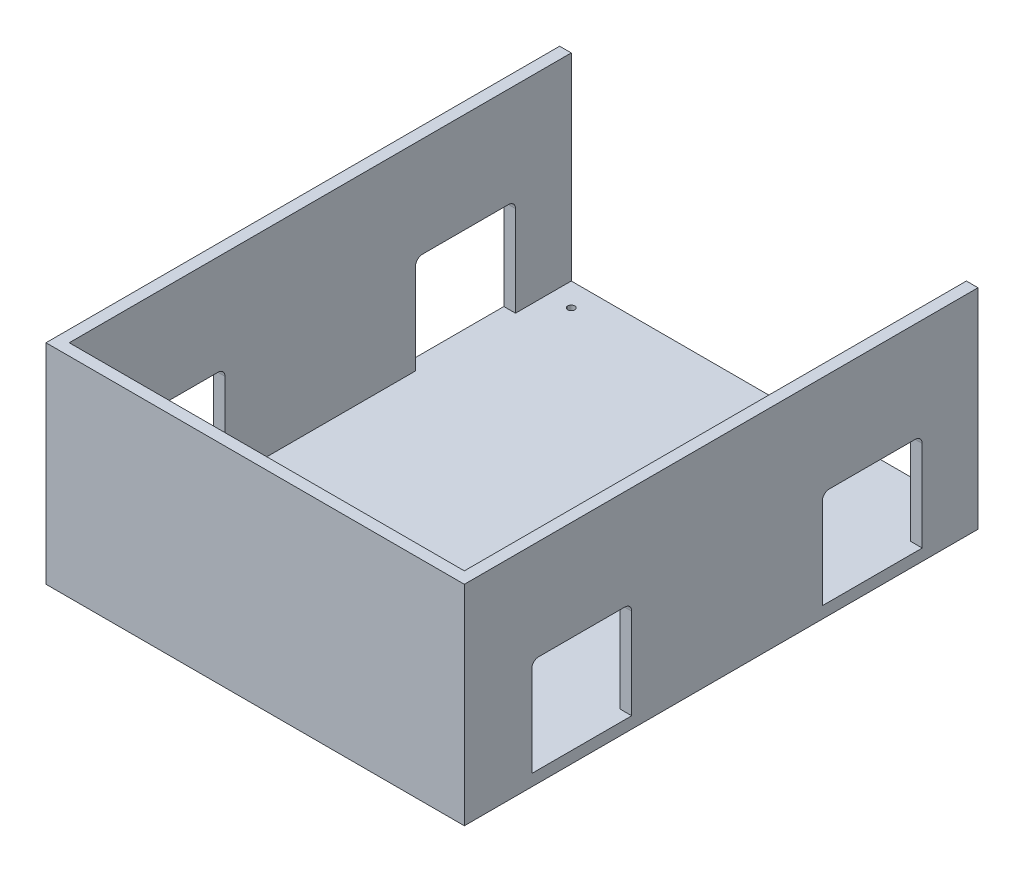
SolidWorks part; units mm, degrees
ref_plane "Front Plane" through (0, 0, 0) normal (0, 0, 1) x (1, 0, 0)
ref_plane "Top Plane" through (0, 0, 0) normal (0, 1, 0) x (1, 0, 0)
ref_plane "Right Plane" through (0, 0, 0) normal (1, 0, 0) x (0, 0, -1)
sketch "Sketch1" plane through (0, 0, 0) normal (0, 1, 0) x (1, 0, 0)
  line L1 (-85, 108) -> (85, 108)
  line L2 (-85, 108) -> (-85, -108)
  line L3 (-85, -108) -> (85, -108)
  line L4 (85, 108) -> (85, -108)
  line L5 (-85, 108) -> (85, -108) construction
  line L6 (-85, -108) -> (85, 108) construction
  point P0 (0, 0)
  dimension "D1" = 216
  dimension "D2" = 170
extrude "Boss-Extrude1" add sketch "Sketch1" along normal blind 5
sketch "Sketch2" plane through (0, 5, 0) normal (0, 1, 0) x (1, 0, 0)
  line L0 (-85, 108) -> (-85, -108) construction
  line L1 (85, 108) -> (-85, 108) construction
  line L2 (-85, -108) -> (85, -108) construction
  line L3 (85, -108) -> (85, 108) construction
  circle A0 centre (-75, 98) radius 1.5
  circle A1 centre (75, 98) radius 1.5
  circle A2 centre (-75, -98) radius 1.5
  circle A3 centre (75, -98) radius 1.5
  dimension "D1" = 3
  dimension "D2" = 3
  dimension "D3" = 3
  dimension "D4" = 3
  dimension "D5" = 10
  dimension "D6" = 10
  dimension "D7" = 10
  dimension "D8" = 10
  dimension "D9" = 10
  dimension "D10" = 10
  dimension "D11" = 10
  dimension "D12" = 10
extrude "Cut-Extrude1" cut sketch "Sketch2" against normal through all
sketch "Sketch9" plane through (0, 0, -108) normal (0, 0, -1) x (-1, 0, 0)
  line L1 (-85, 0) -> (85, 0)
  line L2 (-85, 0) -> (-85, 90)
  line L3 (-85, 90) -> (85, 90)
  line L4 (85, 0) -> (85, 90)
  dimension "D1" = 90
  dimension "D2" = 170
extrude "Boss-Extrude2" add sketch "Sketch9" along normal blind 3
sketch "Sketch10" plane through (85, 0, 0) normal (1, 0, 0) x (0, 0, -1)
  line L0 (-108, 5) -> (-84, 5) construction
  line L1 (-108, 0) -> (111, 0)
  line L2 (-108, 0) -> (-108, 90)
  line L3 (-108, 90) -> (111, 90)
  line L4 (111, 0) -> (111, 90)
  line L5 (-108, 5) -> (108, 5) construction
  line L6 (108, 5) -> (84, 5) construction
  line L7 (-84, 5) -> (-41, 5)
  line L8 (-84, 5) -> (-84, 44)
  line L9 (-81, 47) -> (-44, 47)
  line L10 (-41, 5) -> (-41, 44)
  line L12 (84, 5) -> (41, 5)
  line L13 (84, 5) -> (84, 44)
  line L14 (81, 47) -> (44, 47)
  line L15 (41, 5) -> (41, 44)
  arc A0 (-84, 44) -> (-81, 47) centre (-81, 44) cw
  arc A1 (-44, 47) -> (-41, 44) centre (-44, 44) cw
  arc A2 (44, 47) -> (41, 44) centre (44, 44) ccw
  arc A3 (84, 44) -> (81, 47) centre (81, 44) ccw
  point P22 (-84, 47)
  point P27 (41, 47)
  point P30 (84, 47)
  dimension "D7" = 3
  dimension "D8" = 3
  dimension "D9" = 3
  dimension "D10" = 3
  dimension "D1" = 24
  dimension "D2" = 43
  dimension "D3" = 42
  dimension "D4" = 24
  dimension "D5" = 42
  dimension "D6" = 43
extrude "Boss-Extrude3" add sketch "Sketch10" along normal blind 5
sketch "Sketch11" plane through (-85, 0, 0) normal (-1, 0, 0) x (0, 0, 1)
  line L0 (108, 0) -> (-111, 0)
  line L1 (108, 0) -> (-111, 0)
  line L2 (-111, 0) -> (-111, 90)
  line L3 (-111, 0) -> (-111, 90)
  line L4 (-111, 90) -> (108, 90)
  line L5 (-111, 90) -> (108, 90)
  line L6 (108, 90) -> (108, 0)
  line L7 (108, 90) -> (108, 0)
  line L8 (-84, 5) -> (-84, 44)
  line L9 (-81, 47) -> (-44, 47)
  line L10 (-41, 44) -> (-41, 5)
  line L11 (-41, 5) -> (-84, 5)
  line L12 (41, 5) -> (41, 44)
  line L14 (44, 47) -> (81, 47)
  line L16 (84, 44) -> (84, 5)
  line L17 (84, 44) -> (84, 5) construction
  line L18 (-108, 5) -> (108, 5) construction
  line L19 (84, 5) -> (41, 5)
  arc A0 (-84, 44) -> (-81, 47) centre (-81, 44) cw
  arc A1 (-44, 47) -> (-41, 44) centre (-44, 44) cw
  arc A2 (41, 44) -> (44, 47) centre (44, 44) cw
  arc A3 (81, 47) -> (84, 44) centre (81, 44) cw
extrude "Boss-Extrude5" add sketch "Sketch11" along normal blind 5
sketch "Sketch14" plane through (0, 0, -111) normal (0, 0, -1) x (-1, 0, 0)
  line L1 (-90, 0) -> (90, 0)
  line L2 (-90, 0) -> (-90, 90)
  line L3 (-90, 90) -> (90, 90)
  line L4 (90, 0) -> (90, 90)
extrude "Cut-Extrude2" cut sketch "Sketch14" against normal blind 3
sketch "Sketch15" plane through (0, 0, 108) normal (0, 0, 1) x (1, 0, 0)
  line L1 (-90, 0) -> (90, 0)
  line L2 (-90, 0) -> (-90, 90)
  line L3 (-90, 90) -> (90, 90)
  line L4 (90, 0) -> (90, 90)
extrude "Boss-Extrude6" add sketch "Sketch15" along normal blind 5
